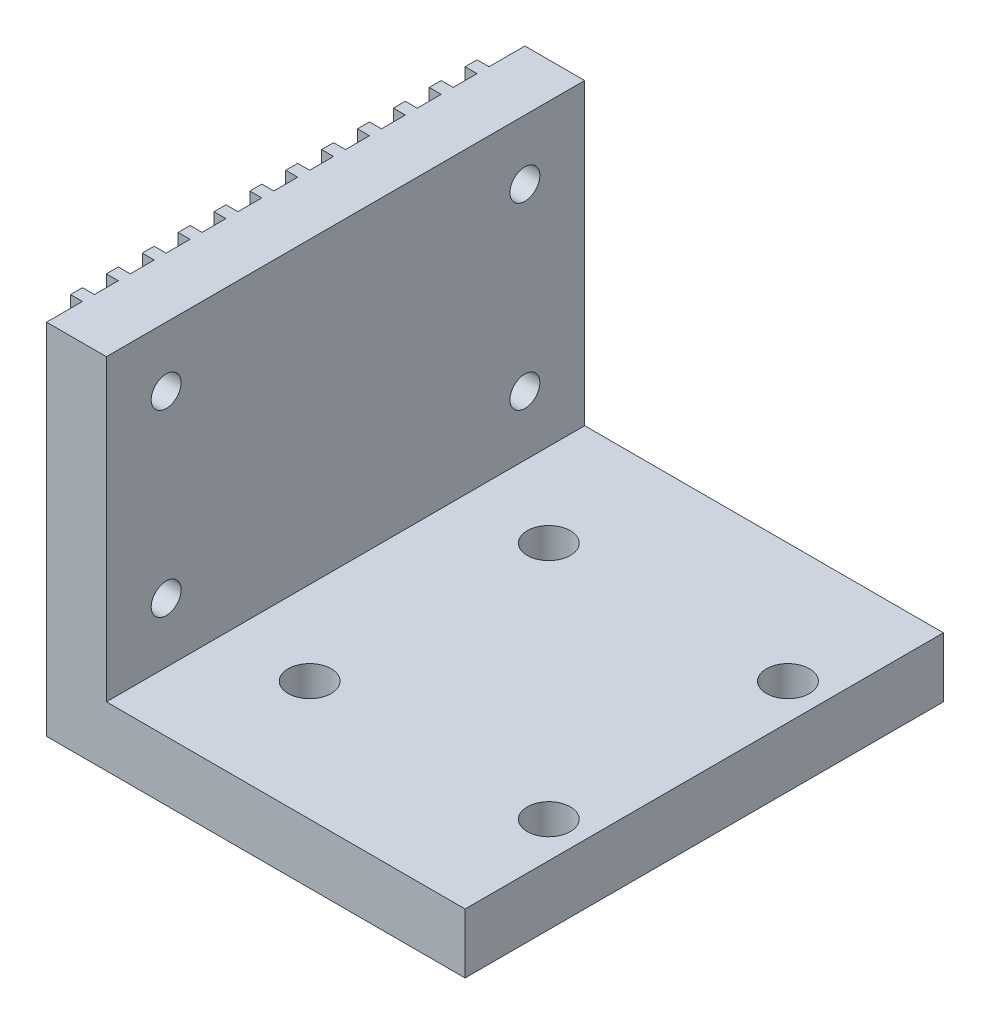
SolidWorks part; units mm, degrees
ref_plane "Plan de face" through (0, 0, 0) normal (0, 0, 1) x (1, 0, 0)
ref_plane "Plan de dessus" through (0, 0, 0) normal (0, 1, 0) x (1, 0, 0)
ref_plane "Plan de droite" through (0, 0, 0) normal (1, 0, 0) x (0, 0, -1)
sketch "Esquisse1" plane through (0, 0, 0) normal (0, 0, 1) x (1, 0, 0)
  line L0 (-17.1785, 11.6667) -> (-17.1785, -18.3333)
  line L1 (-17.1785, -18.3333) -> (17.8215, -18.3333)
  line L2 (17.8215, -18.3333) -> (17.8215, -13.3333)
  line L3 (17.8215, -13.3333) -> (-12.1785, -13.3333)
  line L4 (-12.1785, -13.3333) -> (-12.1785, 11.6667)
  line L5 (-12.1785, 11.6667) -> (-17.1785, 11.6667)
  dimension "D1" = 5
  dimension "D2" = 5
  dimension "D3" = 30
  dimension "D4" = 35
extrude "Boss.-Extru.1" add sketch "Esquisse1" along normal blind 40
sketch "Esquisse2" plane through (-17.1785, 0, 0) normal (-1, 0, 0) x (0, 0, 1)
  line L0 (37, 11.6667) -> (37, -18.3333)
  line L1 (40, 11.6667) -> (0, 11.6667) construction
  line L2 (40, -18.3333) -> (0, -18.3333) construction
  line L3 (40, -3.3333) -> (37, -3.3333) construction
  line L6 (40, 11.6667) -> (40, -18.3333) construction
  dimension "D1" = 3
extrude "Extru.-Mince2" add sketch "Esquisse2" along normal blind 1 thin
pattern_linear "Répétition linéaire1" count 12 spacing 3 along (0, 0, -1) of "Extru.-Mince2"
sketch "Esquisse3" plane through (-12.1785, 0, 0) normal (1, 0, 0) x (0, 0, -1)
  line L0 (-40, 6.6667) -> (0, 6.6667) construction
  line L1 (-40, -13.3333) -> (-40, 11.6667) construction
  line L2 (0, -13.3333) -> (0, 11.6667) construction
  line L3 (-20, 11.6667) -> (-20, 6.6667) construction
  line L4 (-40, 11.6667) -> (0, 11.6667) construction
  line L5 (-20, 6.6667) -> (-20, -8.3333) construction
  line L6 (-40, -8.3333) -> (0, -8.3333) construction
  line L7 (-20, -0.8333) -> (-35, -0.8333) construction
  line L8 (-35, 6.6667) -> (-35, -8.3333) construction
  line L9 (-20, -0.8333) -> (-5, -0.8333) construction
  line L11 (-5, 6.6667) -> (-5, -8.3333) construction
  point P15 (-35, 6.6667)
  point P16 (-35, -8.3333)
  point P19 (-35, 6.6667)
  point P21 (-35, -8.3333)
  point P27 (-5, 6.6667)
  point P28 (-5, -8.3333)
  point P35 (-5, -8.3333)
  point P37 (-5, 6.6667)
  dimension "D1" = 5
  dimension "D2" = 15
  dimension "D3" = 15
  dimension "D4" = 15
hole_wizard "Trou pour taraudage pour trou taraudé M34" positions "Esquisse3" profile "Esquisse4" hole size "M3" standard "ISO" end condition through all
sketch "Esquisse4" plane through (-12.1785, 6.6667, 5) normal (0, 1, 0) x (0, 0, -1)
  line L0 (0, 0) -> (0, 6)
  line L1 (0, 6) -> (1.25, 6)
  line L2 (1.25, 6) -> (1.25, 0)
  line L5 (1.25, 0) -> (0, 0)
  line L11 (0, -6.35) -> (0, 107.95) construction
  dimension "Diamètre du perçage jusqu'au prochain" = 2.5
  dimension "Profondeur du perçage jusqu'au prochain" = 6
sketch "Esquisse5" plane through (0, -13.3333, 0) normal (0, 1, 0) x (1, 0, 0)
  line L0 (17.8215, -10) -> (14.8215, -10) construction
  line L1 (17.8215, -40) -> (17.8215, 0) construction
  line L2 (14.8215, 0) -> (14.8215, -10) construction
  line L3 (17.8215, 0) -> (-12.1785, 0) construction
  line L4 (14.8215, -10) -> (14.8215, -30) construction
  line L5 (14.8215, -30) -> (17.8215, -30) construction
  line L6 (14.8215, -10) -> (-5.1785, -10) construction
  line L7 (14.8215, -30) -> (14.8215, -40) construction
  line L8 (17.8215, -40) -> (-12.1785, -40) construction
  line L9 (14.8215, -30) -> (-5.1785, -30) construction
  point P1 (14.8215, -10)
  point P6 (14.8215, -30)
  point P10 (-5.1785, -10)
  point P14 (-5.1785, -30)
  point P25 (-5.1785, -10)
  point P27 (-5.1785, -30)
  point P29 (14.8215, -30)
  point P31 (14.8215, -10)
  dimension "D1" = 20
  dimension "D2" = 20
  dimension "D3" = 3
  dimension "D4" = 20
  dimension "D5" = 10
  dimension "D6" = 10
hole_wizard "Dégagement M33" positions "Esquisse5" profile "Esquisse6" hole size "M3" standard "ISO" end condition through all
sketch "Esquisse6" plane through (14.8215, -13.3333, 10) normal (1, 0, 0) x (0, 0, 1)
  line L0 (0, 0) -> (0, 5)
  line L1 (0, 5) -> (1.8, 5)
  line L2 (1.8, 5) -> (1.8, 0)
  line L5 (1.8, 0) -> (0, 0)
  line L11 (0, -6.35) -> (0, 107.95) construction
  dimension "Diamètre du perçage jusqu'au prochain" = 3.6
  dimension "Profondeur du perçage jusqu'au prochain" = 5
